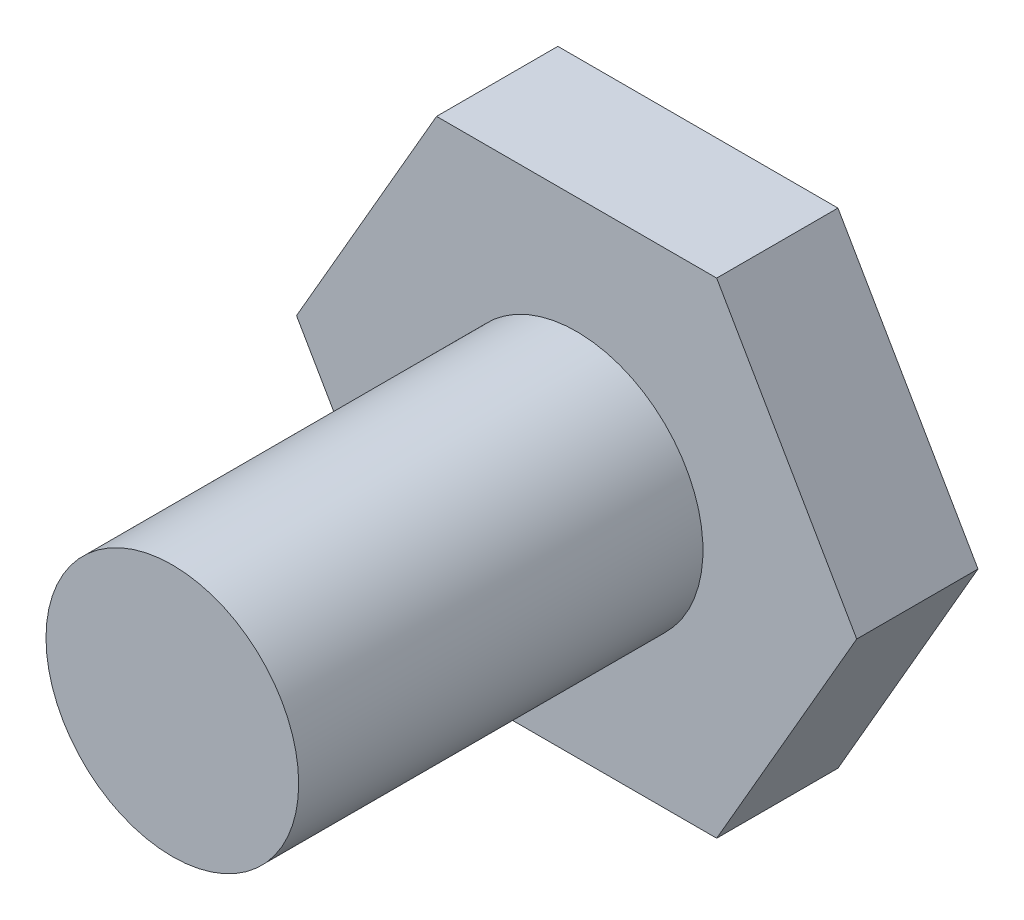
SolidWorks part; units mm, degrees
ref_plane "Front Plane" through (0, 0, 0) normal (0, 0, 1) x (1, 0, 0)
ref_plane "Top Plane" through (0, 0, 0) normal (0, 1, 0) x (1, 0, 0)
ref_plane "Right Plane" through (0, 0, 0) normal (1, 0, 0) x (0, 0, -1)
sketch "Sketch1" plane through (0, 0, 0) normal (0, 0, 1) x (1, 0, 0)
  circle A0 centre (0, 0) radius 31.25
  dimension "D1" = 62.5
extrude "Boss-Extrude1" add sketch "Sketch1" along normal blind 100
sketch "Sketch2" plane through (0, 0, 0) normal (0, 0, -1) x (-1, 0, 0)
  line L1 (69.282, 0) -> (34.641, 60)
  line L2 (34.641, 60) -> (-34.641, 60)
  line L3 (-34.641, 60) -> (-69.282, 0)
  line L4 (-69.282, 0) -> (-34.641, -60)
  line L5 (-34.641, -60) -> (34.641, -60)
  line L6 (34.641, -60) -> (69.282, 0)
  circle A0 centre (0, 0) radius 60 construction
  dimension "D1" = 120
extrude "Boss-Extrude2" add sketch "Sketch2" along normal blind 30
sketch "Sketch3" plane through (0, 0, -30) normal (0, 0, -1) x (-1, 0, 0)
  line L0 (34.641, 60) -> (-34.641, 60) construction
  line L1 (-14.282, 45) -> (14.282, 45)
  line L2 (-14.282, 45) -> (-14.282, -45)
  line L3 (-14.282, -45) -> (14.282, -45)
  line L4 (14.282, 45) -> (14.282, -45)
  line L5 (-34.641, -60) -> (34.641, -60) construction
  point P6 (0, -60)
  dimension "D1" = 15
  dimension "D2" = 15
  dimension "D3" = 55
  dimension "D4" = 55
extrude "Cut-Extrude1" cut sketch "Sketch3" against normal blind 20
